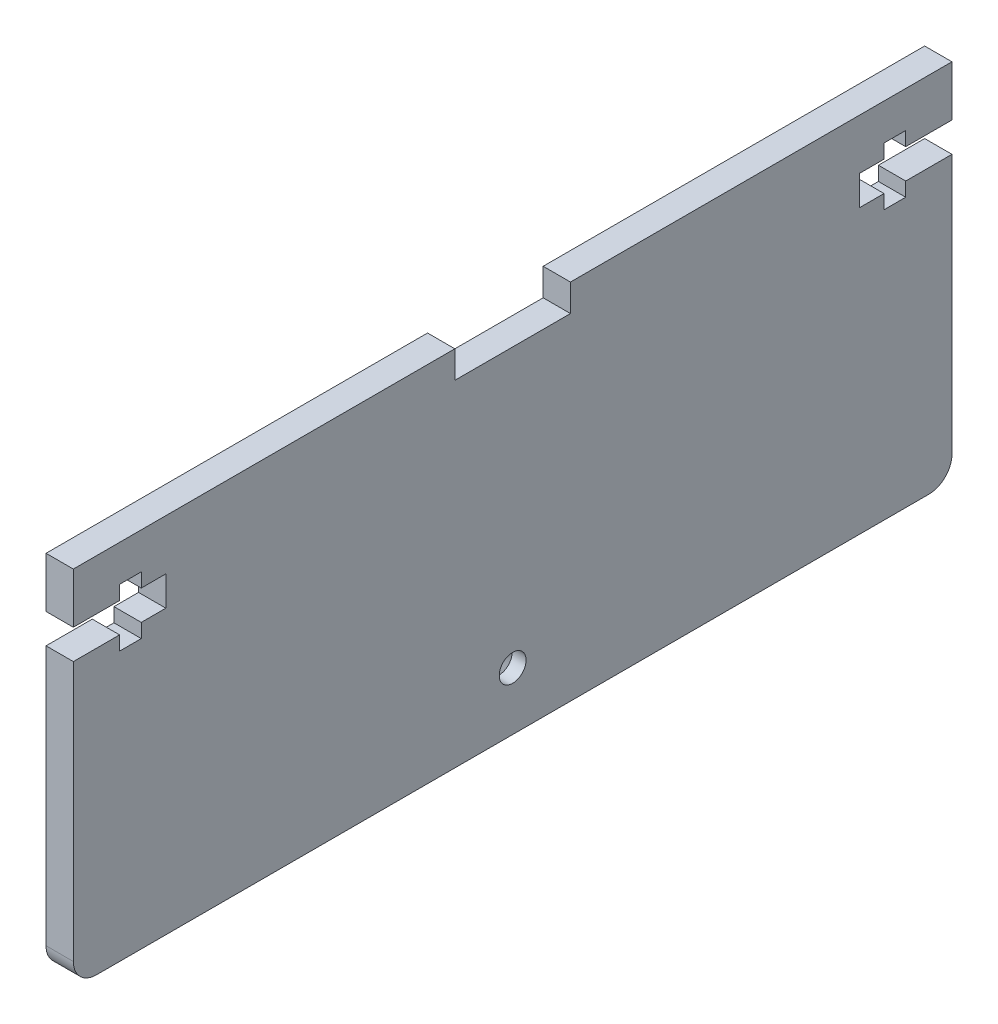
SolidWorks part; units mm, degrees
material "Acrylic (Medium-high impact)"
ref_plane "Front Plane" through (0, 0, 0) normal (0, 0, 1) x (1, 0, 0)
ref_plane "Top Plane" through (0, 0, 0) normal (0, 1, 0) x (1, 0, 0)
ref_plane "Right Plane" through (0, 0, 0) normal (1, 0, 0) x (0, 0, -1)
sketch "Sketch1" plane through (0, 0, 0) normal (1, 0, 0) x (0, 0, -1)
  line L1 (0, 0) -> (96.52, 0)
  line L2 (0, 0) -> (0, 39.878)
  line L3 (0, 39.878) -> (96.52, 39.878)
  line L4 (96.52, 0) -> (96.52, 39.878)
  dimension "D1" = 96.52
  dimension "D2" = 39.878
extrude "Boss-Extrude1" add sketch "Sketch1" along normal blind 3
hole_wizard "#32 (0.116) Diameter Hole1" positions "Sketch3" profile "Sketch2" hole size "#32" standard "ANSI Inch"
sketch "Sketch3" plane through (3, 0, 0) normal (1, 0, 0) x (0, 0, -1)
  line L0 (96.52, 39.878) -> (0, 39.878) construction
  line L1 (96.52, 0) -> (96.52, 39.878) construction
  point P0 (48.26, 6.35)
  dimension "D1" = 33.528
  dimension "D2" = 48.26
sketch "Sketch2" plane through (3, 6.35, -48.26) normal (0, 1, 0) x (0, 0, -1)
  line L0 (0, 0) -> (0, 2.4092)
  line L1 (0, 2.4092) -> (1.4732, 1.524)
  line L2 (1.4732, 1.524) -> (1.4732, 0)
  line L5 (1.4732, 0) -> (0, 0)
  line L10 (0, 2.4092) -> (-1.4732, 1.524) construction
  line L11 (0, -6.35) -> (0, 107.95) construction
  dimension "Hole Dia." = 2.9464
  dimension "Hole Depth" = 1.524
  dimension "Drill Angle" = 118
sketch "Sketch4" plane through (3, 0, 0) normal (1, 0, 0) x (0, 0, -1)
  line L0 (0, 34.338) -> (5.08, 34.338)
  line L1 (0, 39.878) -> (0, 0) construction
  line L2 (5.08, 34.338) -> (5.08, 35.8811)
  line L3 (5.08, 35.8811) -> (7.4613, 35.8811)
  line L4 (7.4613, 35.8811) -> (7.4613, 34.338)
  line L5 (7.4613, 34.338) -> (10.16, 34.338)
  line L6 (10.16, 34.338) -> (10.16, 31.0741)
  line L7 (10.16, 31.0741) -> (7.4613, 31.0741)
  line L8 (7.4613, 31.0741) -> (7.4613, 29.5311)
  line L9 (7.4613, 29.5311) -> (5.08, 29.5311)
  line L10 (5.08, 29.5311) -> (5.08, 31.0741)
  line L11 (5.08, 31.0741) -> (0, 31.0741)
  line L12 (0, 31.0741) -> (0, 34.338)
  line L13 (48.26, 39.878) -> (48.26, 0) construction
  line L14 (96.52, 39.878) -> (0, 39.878) construction
  line L15 (0, 0) -> (96.52, 0) construction
  line L16 (96.52, 31.0741) -> (96.52, 34.338)
  line L17 (91.44, 31.0741) -> (96.52, 31.0741)
  line L18 (91.44, 29.5311) -> (91.44, 31.0741)
  line L19 (89.0587, 29.5311) -> (91.44, 29.5311)
  line L20 (89.0587, 31.0741) -> (89.0587, 29.5311)
  line L21 (86.36, 31.0741) -> (89.0587, 31.0741)
  line L22 (86.36, 34.338) -> (86.36, 31.0741)
  line L23 (89.0587, 34.338) -> (86.36, 34.338)
  line L24 (89.0587, 35.8811) -> (89.0587, 34.338)
  line L25 (91.44, 35.8811) -> (89.0587, 35.8811)
  line L26 (91.44, 34.338) -> (91.44, 35.8811)
  line L27 (96.52, 34.338) -> (91.44, 34.338)
  dimension "D1" = 2.3813
  dimension "D2" = 3.2639
  dimension "D3" = 10.16
  dimension "D4" = 5.08
  dimension "D5" = 6.35
  dimension "D6" = 5.54
extrude "Cut-Extrude1" cut sketch "Sketch4" against normal blind 3
fillet "Fillet1" radius 2.54 2 edges at (1.5, 0, -96.52) (1.5, 0, 0)
sketch "Sketch5" plane through (3, 0, 0) normal (1, 0, 0) x (0, 0, -1)
  line L1 (96.52, 39.878) -> (0, 39.878) construction
  line L2 (41.91, 39.878) -> (54.61, 39.878)
  line L3 (41.91, 39.878) -> (41.91, 36.878)
  line L4 (41.91, 36.878) -> (54.61, 36.878)
  line L6 (54.61, 39.878) -> (54.61, 36.878)
  line L8 (96.52, 34.338) -> (96.52, 39.878) construction
  dimension "D1" = 12.7
  dimension "D2" = 3
  dimension "D3" = 41.91
extrude "Cut-Extrude2" cut sketch "Sketch5" against normal blind 3
sketch "Sketch7" plane through (3, 0, 0) normal (1, 0, 0) x (0, 0, -1)
  line L0 (59.6967, 25.1835) -> (59.4178, 25.8271)
  line L1 (59.4178, 25.8271) -> (59.5417, 26.0404)
  line L2 (66.029, 33.1654) -> (64.4103, 32.2738)
  line L3 (57.57, 28.697) -> (57.3277, 28.5941)
  line L4 (57.3277, 28.5941) -> (56.9418, 28.8044)
  line L5 (33.5282, 21.43) -> (33.1125, 21.3281)
  line L6 (33.1125, 21.3281) -> (33.1429, 20.8582)
  spline S0 degree 3 poles (42.5478, 11.8997) (43.4971, 12.0058) (44.5469, 12.2713) (45.2345, 12.5794) knots 0 0 0 0 1 1 1 1
  spline S1 degree 3 poles (45.2345, 12.5794) (45.7188, 12.7964) (46.1199, 12.874) (46.7593, 12.8745) knots 0 0 0 0 1 1 1 1
  spline S2 degree 3 poles (46.7593, 12.8745) (47.4167, 12.8748) (48.8164, 12.7225) (49.0441, 12.6256) knots 0 0 0 0 1 1 1 1
  spline S3 degree 3 poles (49.0441, 12.6256) (49.1362, 12.5865) (49.4294, 12.5096) (49.6956, 12.4547) knots 0 0 0 0 1 1 1 1
  spline S4 degree 3 poles (49.6956, 12.4547) (50.1195, 12.3673) (50.2864, 12.3577) (51.0405, 12.3769) knots 0 0 0 0 1 1 1 1
  spline S5 degree 3 poles (51.0405, 12.3769) (51.9729, 12.4007) (52.2229, 12.4371) (53.6697, 12.7604) knots 0 0 0 0 1 1 1 1
  spline S6 degree 3 poles (53.6697, 12.7604) (56.3408, 13.3572) (58.0232, 14.1081) (59.1693, 15.2152) knots 0 0 0 0 1 1 1 1
  spline S7 degree 3 poles (59.1693, 15.2152) (59.6023, 15.6334) (59.957, 16.098) (60.1779, 16.5363) knots 0 0 0 0 1 1 1 1
  spline S8 degree 3 poles (60.1779, 16.5363) (60.4231, 17.0226) (60.6868, 17.995) (60.8408, 18.9804) knots 0 0 0 0 1 1 1 1
  spline S9 degree 3 poles (60.8408, 18.9804) (60.9337, 19.5755) (60.9468, 21.051) (60.8646, 21.6699) knots 0 0 0 0 1 1 1 1
  spline S10 degree 3 poles (60.8646, 21.6699) (60.734, 22.6533) (60.4207, 23.7512) (60.1172, 24.289) knots 0 0 0 0 1 1 1 1
  spline S11 degree 3 poles (60.1172, 24.289) (60.0394, 24.427) (59.8501, 24.8295) (59.6967, 25.1835) knots 0 0 0 0 1 1 1 1
  spline S12 degree 3 poles (59.5417, 26.0404) (59.7392, 26.3805) (60.2598, 27.0618) (60.6076, 27.4353) knots 0 0 0 0 1 1 1 1
  spline S13 degree 3 poles (60.6076, 27.4353) (60.7837, 27.6246) (61.4833, 28.2712) (62.1622, 28.8723) knots 0 0 0 0 1 1 1 1
  spline S14 degree 3 poles (62.1622, 28.8723) (63.2021, 29.8508) (66.1413, 32.9044) (66.134, 32.9987) knots 0 0 0 0 1 1 1 1
  spline S15 degree 3 poles (66.134, 32.9987) (66.1342, 33.0159) (66.087, 33.0909) (66.029, 33.1654) knots 0 0 0 0 1 1 1 1
  spline S16 degree 3 poles (64.4103, 32.2738) (61.5806, 30.7152) (58.3733, 29.0381) (57.57, 28.697) knots 0 0 0 0 1 1 1 1
  spline S17 degree 3 poles (56.9418, 28.8044) (55.6762, 29.4938) (54.082, 29.9983) (52.3678, 30.2519) knots 0 0 0 0 1 1 1 1
  spline S18 degree 3 poles (52.3678, 30.2519) (50.8221, 30.4805) (47.8381, 30.4809) (46.3901, 30.2528) knots 0 0 0 0 1 1 1 1
  spline S19 degree 3 poles (46.3901, 30.2528) (44.2843, 29.921) (42.2728, 28.8472) (40.9585, 27.3533) knots 0 0 0 0 1 1 1 1
  spline S20 degree 3 poles (40.9585, 27.3533) (40.5699, 26.9115) (39.855, 25.8568) (39.5517, 25.2776) knots 0 0 0 0 1 1 1 1
  spline S21 degree 3 poles (39.5517, 25.2776) (39.0441, 24.3085) (38.6047, 23.0156) (38.3893, 21.8574) knots 0 0 0 0 1 1 1 1
  spline S22 degree 3 poles (38.3893, 21.8574) (38.2733, 21.2339) (38.243, 20.9246) (38.2397, 20.3347) knots 0 0 0 0 1 1 1 1
  spline S23 degree 3 poles (38.2397, 20.3347) (38.2372, 19.8645) (38.2355, 19.8577) (38.0973, 19.7414) knots 0 0 0 0 1 1 1 1
  spline S24 degree 3 poles (38.0973, 19.7414) (37.7033, 19.4099) (37.4435, 19.5204) (36.2576, 20.5241) knots 0 0 0 0 1 1 1 1
  spline S25 degree 3 poles (36.2576, 20.5241) (35.4342, 21.221) (34.7709, 21.5319) (34.1077, 21.5319) knots 0 0 0 0 1 1 1 1
  spline S26 degree 3 poles (34.1077, 21.5319) (34.0176, 21.5319) (33.7569, 21.4861) (33.5282, 21.43) knots 0 0 0 0 1 1 1 1
  spline S27 degree 3 poles (33.1429, 20.8582) (33.1596, 20.5998) (33.1937, 20.2635) (33.2186, 20.1109) knots 0 0 0 0 1 1 1 1
  spline S28 degree 3 poles (33.2186, 20.1109) (33.2436, 19.9583) (33.2642, 19.7214) (33.2643, 19.5845) knots 0 0 0 0 1 1 1 1
  spline S29 degree 3 poles (33.2643, 19.5845) (33.2646, 19.3651) (33.2472, 19.3194) (33.1177, 19.1985) knots 0 0 0 0 1 1 1 1
  spline S30 degree 3 poles (33.1177, 19.1985) (32.9342, 19.0271) (32.4908, 18.8118) (31.2174, 18.2759) knots 0 0 0 0 1 1 1 1
  spline S31 degree 3 poles (31.2174, 18.2759) (30.1004, 17.8058) (29.9609, 17.7099) (29.9487, 17.4045) knots 0 0 0 0 1 1 1 1
  spline S32 degree 3 poles (29.9487, 17.4045) (29.9386, 17.1519) (30.0874, 16.9355) (30.4723, 16.643) knots 0 0 0 0 1 1 1 1
  spline S33 degree 3 poles (30.4723, 16.643) (31.0365, 16.2141) (32.2663, 15.6936) (32.9851, 15.5793) knots 0 0 0 0 1 1 1 1
  spline S34 degree 3 poles (32.9851, 15.5793) (33.872, 15.4383) (35.679, 15.3897) (36.6148, 15.4817) knots 0 0 0 0 1 1 1 1
  spline S35 degree 3 poles (36.6148, 15.4817) (37.9843, 15.6163) (38.1827, 15.6264) (38.5462, 15.5805) knots 0 0 0 0 1 1 1 1
  spline S36 degree 3 poles (38.5462, 15.5805) (39.1968, 15.4983) (39.7327, 15.2862) (39.7327, 15.1108) knots 0 0 0 0 1 1 1 1
  spline S37 degree 3 poles (39.7327, 15.1108) (39.7327, 15.0193) (39.4861, 14.909) (38.853, 14.7172) knots 0 0 0 0 1 1 1 1
  spline S38 degree 3 poles (38.853, 14.7172) (38.1351, 14.4998) (38.0003, 14.4304) (37.8928, 14.2224) knots 0 0 0 0 1 1 1 1
  spline S39 degree 3 poles (37.8928, 14.2224) (37.7934, 14.0304) (37.8646, 13.8212) (38.1195, 13.5563) knots 0 0 0 0 1 1 1 1
  spline S40 degree 3 poles (38.1195, 13.5563) (38.2261, 13.4456) (38.3865, 13.2533) (38.4761, 13.1289) knots 0 0 0 0 1 1 1 1
  spline S41 degree 3 poles (38.4761, 13.1289) (39.1609, 12.1782) (40.7489, 11.6988) (42.5478, 11.8997) knots 0 0 0 0 1 1 1 1
  point P0 (0, 0.001)
  point P1 (0.001, 0.001)
  point P2 (0.001, 0)
